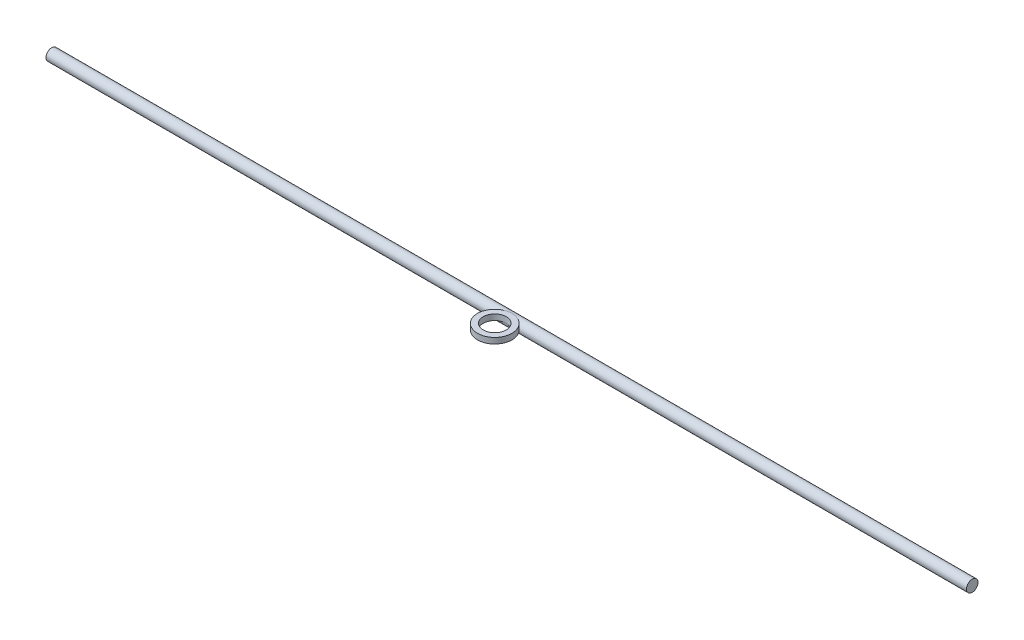
SolidWorks part; units mm, degrees
ref_plane "Plan de face" through (0, 0, 0) normal (0, 0, 1) x (1, 0, 0)
ref_plane "Plan de dessus" through (0, 0, 0) normal (0, 1, 0) x (1, 0, 0)
ref_plane "Plan de droite" through (0, 0, 0) normal (1, 0, 0) x (0, 0, -1)
sketch "Esquisse1" plane through (0, 0, 0) normal (0, 0, 1) x (1, 0, 0)
  line L0 (-400, 0) -> (400, 0)
  dimension "D1" = 800
sweep "Balayage1" add path "Esquisse1" circular profile diameter 10 parameters "D3"=10
sketch "Esquisse2" plane through (0, 0, 0) normal (0, 1, 0) x (1, 0, 0)
  line L0 (-400, -5) -> (400, -5) construction
  circle A0 centre (0, -15) radius 10
  circle A1 centre (0, -15) radius 15
  dimension "D1" = 20
  dimension "D2" = 5
extrude "Boss.-Extru.1" add sketch "Esquisse2" along normal blind 5
